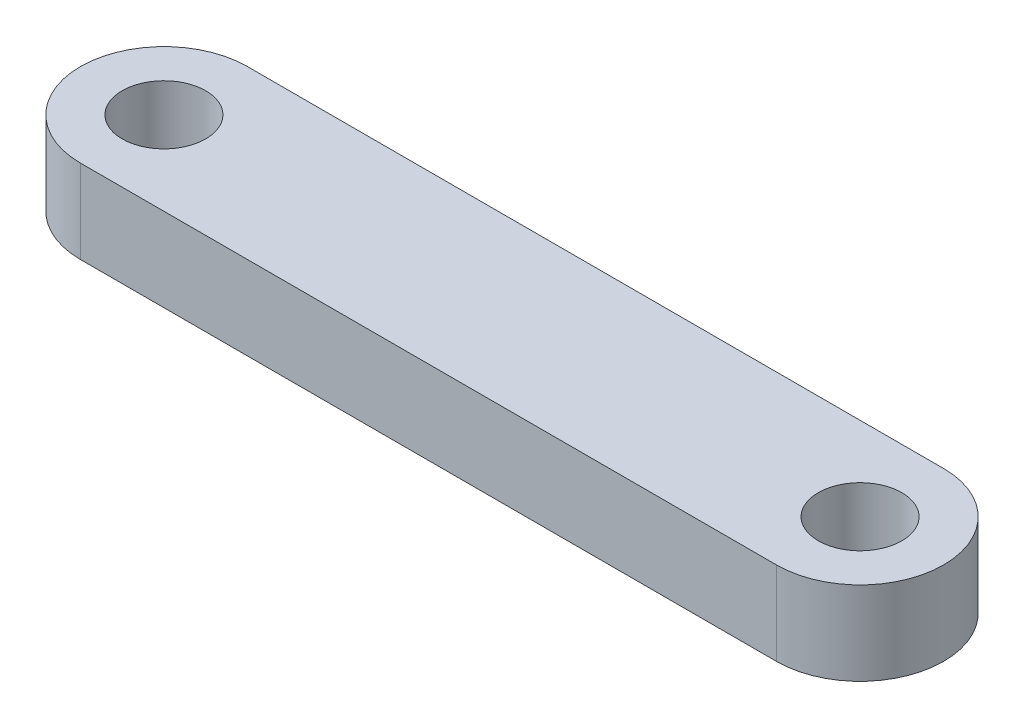
SolidWorks part; units mm, degrees
ref_plane "Front Plane" through (0, 0, 0) normal (0, 0, 1) x (1, 0, 0)
ref_plane "Top Plane" through (0, 0, 0) normal (0, 1, 0) x (1, 0, 0)
ref_plane "Right Plane" through (0, 0, 0) normal (1, 0, 0) x (0, 0, -1)
sketch "Sketch2" plane through (0, 0, 0) normal (0, 1, 0) x (1, 0, 0)
  line L0 (0, -12.5) -> (0, 12.5)
  line L1 (0, -12.5) -> (-25, -12.5)
  line L2 (0, 12.5) -> (25, 12.5)
  line L3 (0, 0) -> (-12.4066, 38.0273)
  line L4 (-12.4066, 38.0273) -> (-32, 22.5)
  line L5 (-32, 22.5) -> (-52.7065, 30.7)
  line L6 (-52.7065, 30.7) -> (-30.6151, 86.485)
  line L7 (-12, 27.5) -> (-10.6151, 91.485)
  line L8 (-32, 22.5) -> (-30.6151, 86.485) construction
  line L9 (-10.6151, 91.485) -> (-30.6151, 86.485)
  line L10 (0, -57.9364) -> (0, 57.9364) construction
  line L11 (0, 0) -> (12.4066, 38.0273)
  line L12 (32, 22.5) -> (30.6151, 86.485) construction
  line L13 (10.6151, 91.485) -> (30.6151, 86.485)
  line L14 (12, 27.5) -> (10.6151, 91.485)
  line L15 (52.7065, 30.7) -> (30.6151, 86.485)
  line L16 (32, 22.5) -> (52.7065, 30.7)
  line L17 (12.4066, 38.0273) -> (32, 22.5)
  line L18 (-25, -6.5) -> (-25, -46.5) construction
  line L19 (-15, -6.5) -> (-35, -6.5)
  line L20 (-15, -6.5) -> (-15, -46.5)
  line L21 (-15, -46.5) -> (-35, -46.5)
  line L22 (-35, -6.5) -> (-35, -46.5)
  circle A0 centre (25, 12.5) radius 1.5
  circle A1 centre (-25, -12.5) radius 1.5
  circle A2 centre (-12, 27.5) radius 1.5
  circle A3 centre (-32, 22.5) radius 1.5
  circle A4 centre (32, 22.5) radius 1.5
  circle A5 centre (12, 27.5) radius 1.5
  circle A6 centre (-25, -12.5) radius 9.2314
  point P15 (0, 0)
  dimension "D3" = 3
  dimension "D1" = 25
  dimension "D2" = 25
  dimension "D5" = 12.5
  dimension "D4" = 12.5
  dimension "D6" = 25
  dimension "D7" = 25
  dimension "D8" = 40
  dimension "D10" = 25
  dimension "D11" = 120
  dimension "D15" = 20
  dimension "D17" = 40
  dimension "D9" = 12
  dimension "D14" = 5
  dimension "D13" = 64
  dimension "D12" = 60
  dimension "D16" = 40
  dimension "D18" = 20
  dimension "D19" = 6
sketch "Sketch3" plane through (0, 0, 0) normal (0, 1, 0) x (1, 0, 0)
  line L0 (0, 12.5) -> (25, 12.5) construction
  line L1 (0, 15.5) -> (25, 15.5)
  line L2 (0, 9.5) -> (25, 9.5)
  arc A0 (0, 15.5) -> (0, 9.5) centre (0, 12.5) ccw
  arc A1 (25, 9.5) -> (25, 15.5) centre (25, 12.5) ccw
  circle A2 centre (25, 12.5) radius 1.5
  circle A3 centre (0, 12.5) radius 1.5
  point P4 (12.5, 12.5)
  dimension "D1" = 3
  dimension "D2" = 3
extrude "Boss-Extrude1" add sketch "Sketch3" along normal blind 3
equation "\"a\"= \"b\" / 2"
equation "\"b\"= 25"
equation "\"D1@Sketch2\"=2*\"a\""
equation "\"D2@Sketch2\"=\"b\""
equation "\"D5@Sketch2\"=\"a\""
equation "\"D4@Sketch2\"=\"a\""
equation "\"D6@Sketch2\"=\"b\""
equation "\"D7@Sketch2\"=\"b\""
equation "\"c\"= 64"
equation "\"D13@Sketch2\"=\"c\""
equation "\"D12@Sketch2\"=\"c\"-4"
